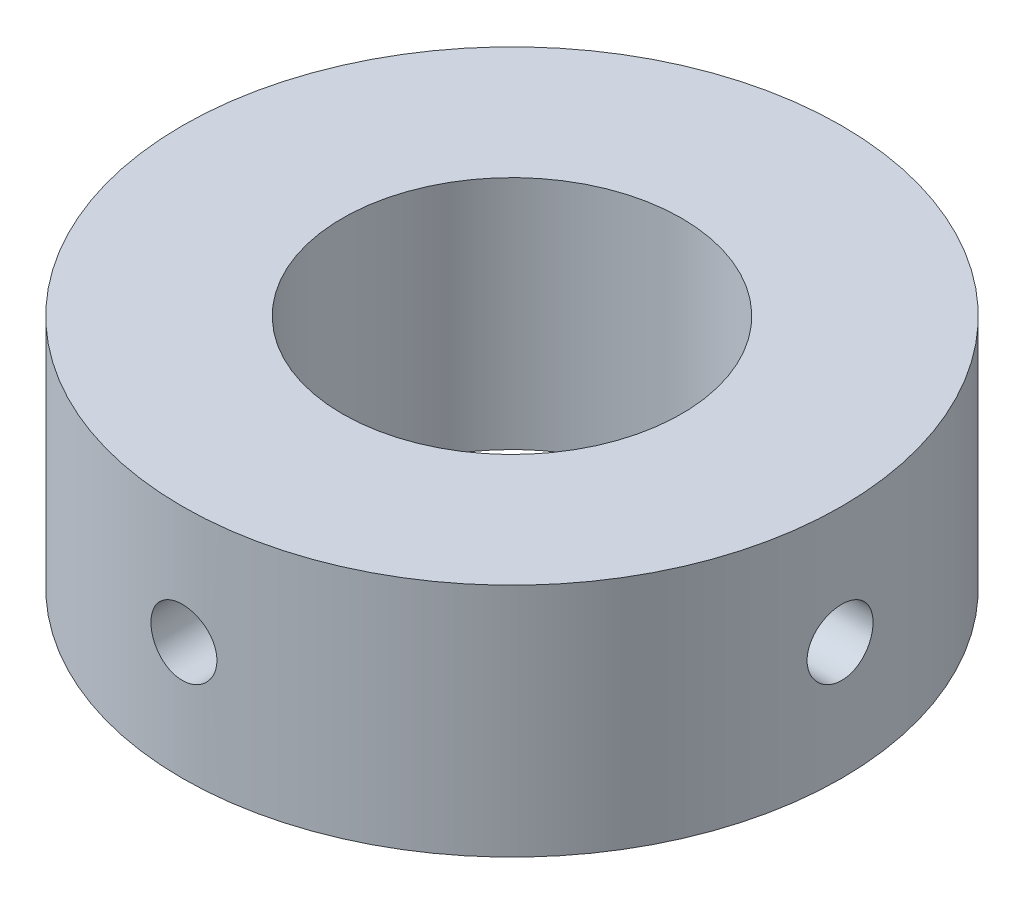
SolidWorks part; units mm, degrees
material "6061 Alloy"
ref_plane "Front Plane" through (0, 0, 0) normal (0, 0, 1) x (1, 0, 0)
ref_plane "Top Plane" through (0, 0, 0) normal (0, 1, 0) x (1, 0, 0)
ref_plane "Right Plane" through (0, 0, 0) normal (1, 0, 0) x (0, 0, -1)
sketch "Sketch1" plane through (0, 0, 0) normal (0, 1, 0) x (1, 0, 0)
  circle A0 centre (0, 0) radius 4.572
  circle A1 centre (0, 0) radius 8.89
  dimension "D1" = 9.144
  dimension "D2" = 17.78
extrude "Boss-Extrude1" add sketch "Sketch1" along normal blind 6.35
sketch "Sketch2" plane through (0, 0, 0) normal (1, 0, 0) x (0, 0, -1)
  line L0 (0, 0) -> (0, 6.35) construction
  line L1 (4.572, 6.35) -> (-4.572, 6.35) construction
  circle A0 centre (0, 3.175) radius 0.889
  dimension "D1" = 1.778
extrude "Cut-Extrude1" cut sketch "Sketch2" along normal up to next
sketch "Sketch3" plane through (0, 0, 0) normal (0, 0, 1) x (1, 0, 0)
  line L0 (0, 6.35) -> (0, 0) construction
  line L1 (4.572, 6.35) -> (-4.572, 6.35) construction
  line L2 (-8.89, 0) -> (8.89, 0) construction
  circle A0 centre (0, 3.175) radius 0.889
  dimension "D1" = 1.778
extrude "Cut-Extrude2" cut sketch "Sketch3" along normal up to next
